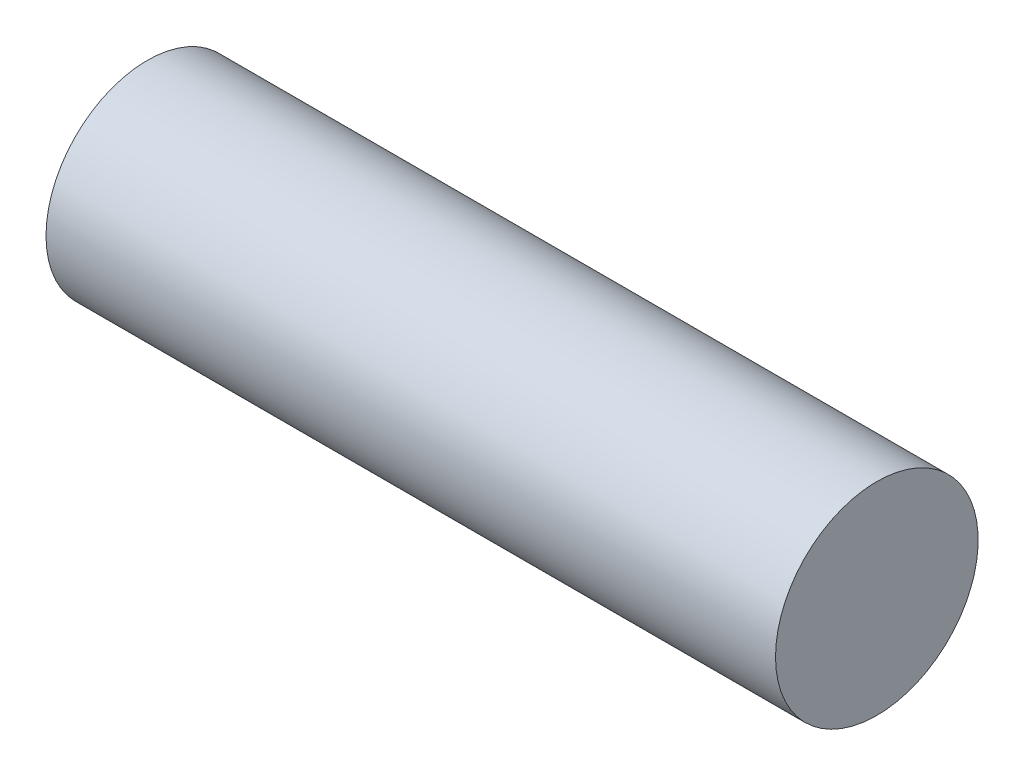
SolidWorks part; units mm, degrees
ref_plane "Front Plane" through (0, 0, 0) normal (0, 0, 1) x (1, 0, 0)
ref_plane "Top Plane" through (0, 0, 0) normal (0, 1, 0) x (1, 0, 0)
ref_plane "Right Plane" through (0, 0, 0) normal (1, 0, 0) x (0, 0, -1)
sketch "Sketch1" plane through (0, 0, 0) normal (1, 0, 0) x (0, 0, -1)
  circle A0 centre (0, 0) radius 50
  dimension "D1" = 100
extrude "Boss-Extrude1" add sketch "Sketch1" along normal blind 360
